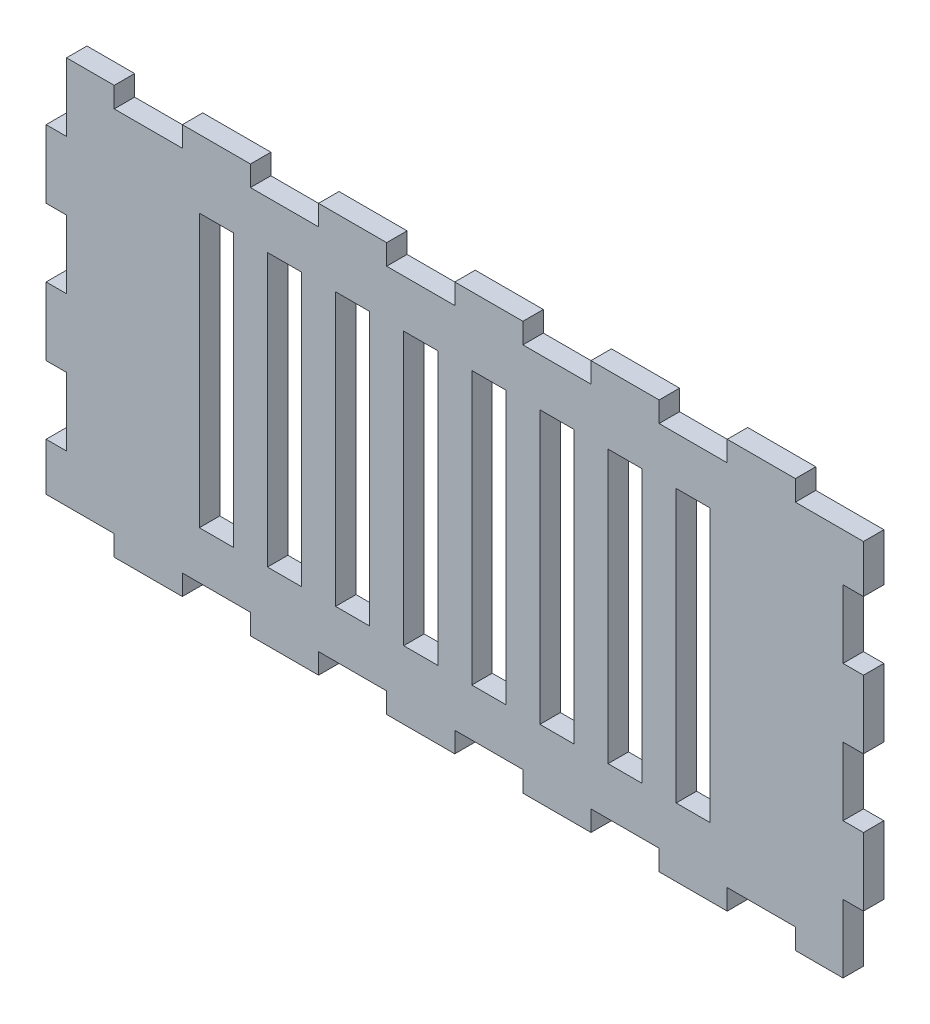
SolidWorks part; units mm, degrees
material "Beech"
ref_plane "Front Plane" through (0, 0, 0) normal (0, 0, 1) x (1, 0, 0)
ref_plane "Top Plane" through (0, 0, 0) normal (0, 1, 0) x (1, 0, 0)
ref_plane "Right Plane" through (0, 0, 0) normal (1, 0, 0) x (0, 0, -1)
sketch "Sketch1" plane through (0, 0, 0) normal (0, 0, 1) x (1, 0, 0)
  line L0 (120, 0) -> (117, 0)
  line L1 (0, 0) -> (120, 0)
  line L2 (0, 0) -> (0, 60)
  line L3 (0, 60) -> (120, 60)
  line L4 (120, 0) -> (120, 60)
  line L5 (117, 0) -> (117, 10)
  line L6 (117, 10) -> (120, 10)
  line L7 (117, 30) -> (120, 30)
  line L8 (117, 20) -> (117, 30)
  line L9 (120, 20) -> (117, 20)
  line L10 (117, 50) -> (120, 50)
  line L11 (117, 40) -> (117, 50)
  line L12 (120, 40) -> (117, 40)
  line L13 (3, 3) -> (10, 3)
  line L14 (10, 3) -> (10, 0)
  line L15 (20, 0) -> (20, 3)
  line L16 (20, 3) -> (30, 3)
  line L17 (30, 3) -> (30, 0)
  line L18 (40, 0) -> (40, 3)
  line L19 (40, 3) -> (50, 3)
  line L20 (50, 3) -> (50, 0)
  line L21 (60, 0) -> (60, 3)
  line L22 (60, 3) -> (70, 3)
  line L23 (70, 3) -> (70, 0)
  line L24 (80, 0) -> (80, 3)
  line L25 (80, 3) -> (90, 3)
  line L26 (90, 3) -> (90, 0)
  line L27 (100, 0) -> (100, 3)
  line L28 (100, 3) -> (110, 3)
  line L29 (110, 3) -> (110, 0)
  line L30 (110, 60) -> (110, 57)
  line L31 (110, 57) -> (117, 57)
  line L32 (100, 60) -> (100, 57)
  line L33 (100, 57) -> (90, 57)
  line L34 (0, 60) -> (3, 60)
  line L35 (3, 60) -> (3, 50)
  line L36 (3, 50) -> (0, 50)
  line L37 (3, 30) -> (0, 30)
  line L38 (3, 40) -> (3, 30)
  line L39 (0, 40) -> (3, 40)
  line L40 (3, 10) -> (0, 10)
  line L41 (3, 20) -> (3, 10)
  line L42 (0, 20) -> (3, 20)
  line L43 (90, 57) -> (90, 60)
  line L44 (80, 60) -> (80, 57)
  line L45 (80, 57) -> (70, 57)
  line L46 (70, 57) -> (70, 60)
  line L47 (60, 60) -> (60, 57)
  line L48 (60, 57) -> (50, 57)
  line L49 (50, 57) -> (50, 60)
  line L50 (40, 60) -> (40, 57)
  line L51 (40, 57) -> (30, 57)
  line L52 (30, 57) -> (30, 60)
  line L53 (20, 60) -> (20, 57)
  line L54 (20, 57) -> (10, 57)
  line L55 (10, 57) -> (10, 60)
  line L56 (3, 3) -> (0, 3)
  line L57 (117, 57) -> (120, 57)
  point P45 (110, 58.5)
  dimension "D1" = 120
  dimension "D2" = 60
  dimension "D3" = 5
  dimension "D4" = 0
  dimension "D5" = 10
  dimension "D7" = 10
  dimension "D8" = 3
  dimension "D9" = 10
  dimension "D11" = 0
  dimension "D12" = 10
  dimension "D13" = 3
  dimension "D10" = 10
  dimension "D15" = 3
  dimension "D16" = 3
  dimension "D17" = 10
  dimension "D18" = 10
  dimension "D19" = 10
  dimension "D20" = 3
  dimension "D22" = 5
  dimension "D14" = 3
  dimension "D6" = 3
extrude "Boss-Extrude1" add sketch "Sketch1" along normal blind 3
sketch "Sketch2" plane through (0, 0, 3) normal (0, 0, 1) x (1, 0, 0)
  line L0 (3, 60) -> (10, 60) construction
  line L1 (22.5, 50) -> (27.5, 50)
  line L2 (22.5, 50) -> (22.5, 10)
  line L3 (22.5, 10) -> (27.5, 10)
  line L4 (27.5, 50) -> (27.5, 10)
  line L5 (0, 40) -> (0, 50) construction
  line L6 (32.5, 50) -> (32.5, 10)
  line L7 (32.5, 50) -> (37.5, 50)
  line L8 (37.5, 50) -> (37.5, 10)
  line L9 (32.5, 10) -> (37.5, 10)
  line L10 (42.5, 50) -> (42.5, 10)
  line L11 (42.5, 50) -> (47.5, 50)
  line L12 (47.5, 50) -> (47.5, 10)
  line L13 (42.5, 10) -> (47.5, 10)
  line L14 (52.5, 50) -> (52.5, 10)
  line L15 (52.5, 50) -> (57.5, 50)
  line L16 (57.5, 50) -> (57.5, 10)
  line L17 (52.5, 10) -> (57.5, 10)
  line L18 (62.5, 50) -> (62.5, 10)
  line L19 (62.5, 50) -> (67.5, 50)
  line L20 (67.5, 50) -> (67.5, 10)
  line L21 (62.5, 10) -> (67.5, 10)
  line L22 (72.5, 50) -> (72.5, 10)
  line L23 (72.5, 50) -> (77.5, 50)
  line L24 (77.5, 50) -> (77.5, 10)
  line L25 (72.5, 10) -> (77.5, 10)
  line L26 (82.5, 50) -> (82.5, 10)
  line L27 (82.5, 50) -> (87.5, 50)
  line L28 (87.5, 50) -> (87.5, 10)
  line L29 (82.5, 10) -> (87.5, 10)
  line L30 (92.5, 50) -> (92.5, 10)
  line L31 (92.5, 50) -> (97.5, 50)
  line L32 (97.5, 50) -> (97.5, 10)
  line L33 (92.5, 10) -> (97.5, 10)
  dimension "D1" = 5
  dimension "D2" = 40
  dimension "D3" = 10
  dimension "D4" = 22.5
extrude "Cut-Extrude1" cut sketch "Sketch2" against normal blind 10
